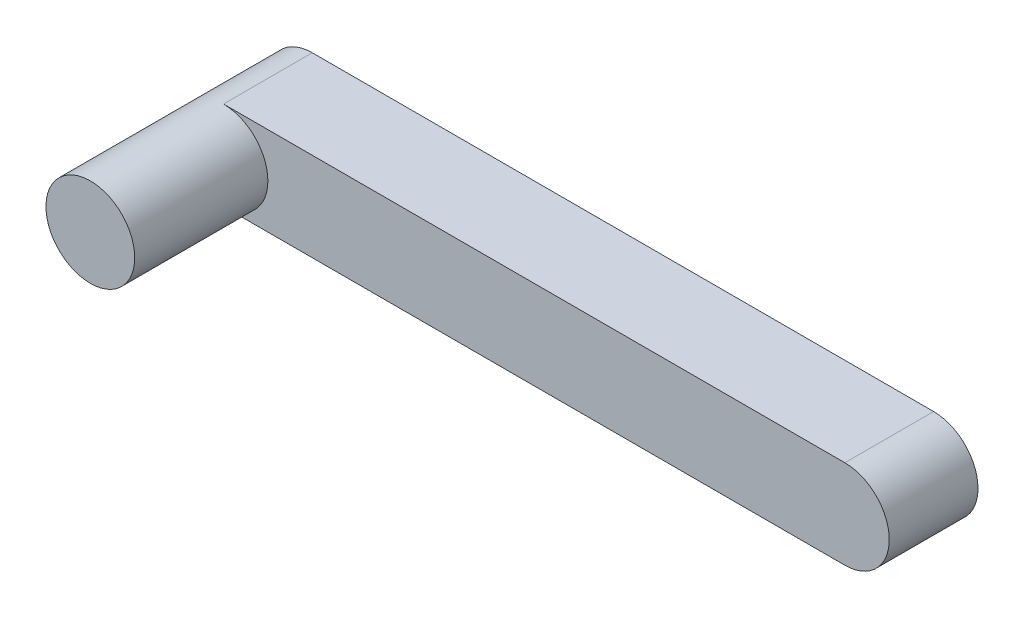
SolidWorks part; units mm, degrees
ref_plane "Front Plane" through (0, 0, 0) normal (0, 0, 1) x (1, 0, 0)
ref_plane "Top Plane" through (0, 0, 0) normal (0, 1, 0) x (1, 0, 0)
ref_plane "Right Plane" through (0, 0, 0) normal (1, 0, 0) x (0, 0, -1)
sketch "Sketch1" plane through (0, 0, 0) normal (0, 0, 1) x (1, 0, 0)
  line L0 (0, 0) -> (-177.8, 0) construction
  line L1 (0, -12.7) -> (-177.8, -12.7)
  line L2 (0, 12.7) -> (-177.8, 12.7)
  arc A0 (0, -12.7) -> (0, 12.7) centre (0, 0) ccw
  arc A1 (-177.8, 12.7) -> (-177.8, -12.7) centre (-177.8, 0) ccw
  point P3 (-88.9, 0)
  point P8 (-190.5, 0)
  point P9 (12.7, 0)
  dimension "D1" = 25.4
  dimension "D2" = 203.2
extrude "Boss-Extrude1" add sketch "Sketch1" along normal blind 25.4
sketch "Sketch2" plane through (0, 0, 25.4) normal (0, 0, 1) x (1, 0, 0)
  circle A0 centre (-177.8, 0) radius 12.7
  arc A1 (-177.8, 12.7) -> (-177.8, -12.7) centre (-177.8, 0) ccw construction
extrude "Boss-Extrude2" add sketch "Sketch2" along normal blind 38.1
